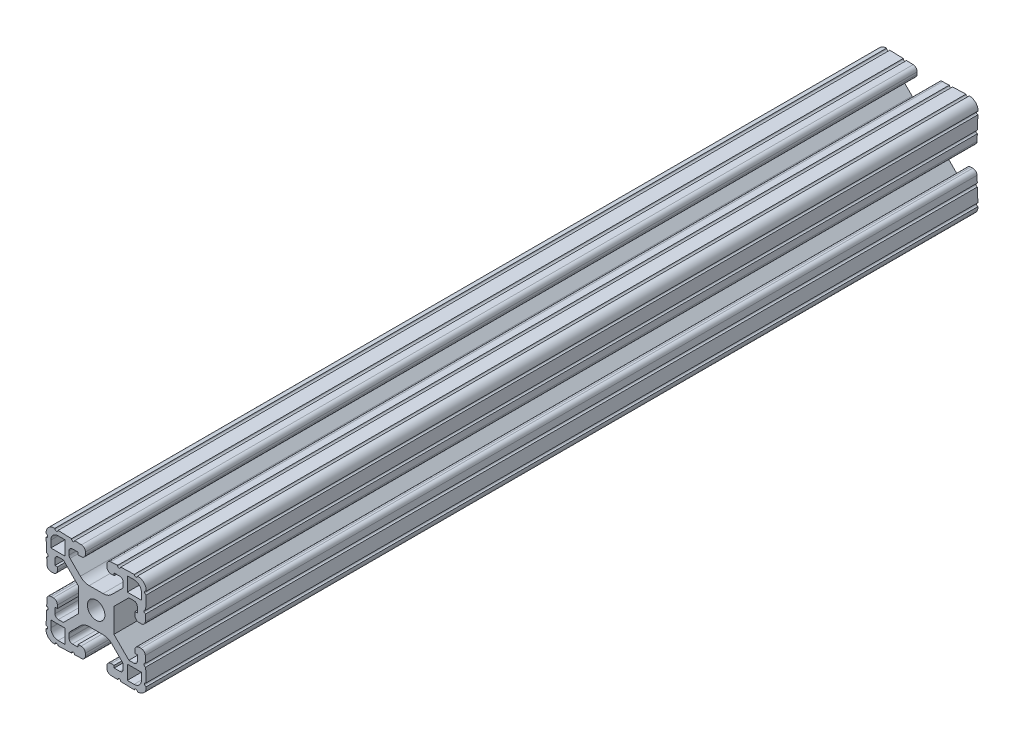
SolidWorks part; units mm, degrees
ref_plane "Front Plane" through (0, 0, 0) normal (0, 0, 1) x (1, 0, 0)
ref_plane "Top Plane" through (0, 0, 0) normal (0, 1, 0) x (1, 0, 0)
ref_plane "Right Plane" through (0, 0, 0) normal (1, 0, 0) x (0, 0, -1)
sketch "Sketch1" plane through (0, 0, 0) normal (0, 0, 1) x (1, 0, 0)
  line L0 (0, 19.05) -> (-19.1669, 19.05) construction
  line L1 (-6.7564, 0) -> (-6.7564, 4.6011)
  line L2 (-8.7357, 18.8026) -> (-15.7642, 19.0481) construction
  line L3 (-17.655, 18.5041) -> (-4.0303, 18.0283) construction
  line L4 (-5.5829, 18.6925) -> (-5.7212, 14.7325) construction
  line L5 (-11.8364, 17.2212) -> (-11.8364, 11.8364)
  line L6 (-2.6337, 6.7564) -> (0, 6.7564)
  line L7 (0, 0) -> (0, 19.05) construction
  line L8 (0, 0) -> (-19.1669, 0) construction
  line L9 (1.0776, 1.0776) -> (-1.0776, -1.0776) construction
  line L10 (-5.9923, 8.1476) -> (-9.915, 12.0703)
  line L11 (-6.7564, 4.6011) -> (-12.4423, 10.287)
  line L12 (-11.8364, 11.8364) -> (-17.2212, 11.8364)
  line L13 (0, 0) -> (-19.1669, 19.1669) construction
  line L14 (-15.7642, 19.0481) -> (-5.5829, 18.6925)
  line L15 (-4.064, 17.0637) -> (-4.0924, 16.2514)
  line L17 (-19.0481, 15.7642) -> (-18.6925, 5.5829)
  line L19 (-17.2212, 11.8364) -> (-17.2212, 14.4272)
  line L20 (-11.8364, 17.2212) -> (-14.4272, 17.2212)
  line L21 (-10.287, 12.9683) -> (-10.287, 14.3745)
  line L22 (-14.3745, 10.287) -> (-12.4423, 10.287)
  line L23 (-9.017, 15.6445) -> (-6.858, 15.6445)
  line L24 (-6.858, 15.6445) -> (-6.858, 14.7325)
  line L25 (-5.7212, 14.7325) -> (-6.858, 14.7325)
  line L26 (-17.0637, 4.064) -> (-16.2514, 4.0924)
  line L27 (-14.7325, 5.7212) -> (-14.7325, 6.858)
  line L28 (-15.6445, 6.858) -> (-14.7325, 6.858)
  line L29 (-15.6445, 9.017) -> (-15.6445, 6.858)
  circle A0 centre (0, 0) radius 3.3274
  arc A5 (-15.7642, 19.0481) -> (-19.0481, 15.7642) centre (-15.875, 15.875) ccw
  arc A7 (-9.3449, 18.8239) -> (-8.1264, 18.7813) centre (-8.7357, 18.8026) ccw
  arc A10 (-17.2212, 14.4272) -> (-14.4272, 17.2212) centre (-14.4272, 14.4272) cw
  arc A11 (-4.0924, 16.2514) -> (-5.7212, 14.7325) centre (-5.6662, 16.3064) cw
  arc A12 (-5.5829, 18.6925) -> (-4.064, 17.0637) centre (-5.6378, 17.1187) cw
  arc A13 (-5.9923, 8.1476) -> (-2.6337, 6.7564) centre (-2.6337, 11.5062) ccw
  arc A14 (-9.915, 12.0703) -> (-10.287, 12.9683) centre (-9.017, 12.9683) cw
  arc A15 (-10.287, 14.3745) -> (-9.017, 15.6445) centre (-9.017, 14.3745) cw
  arc A16 (-15.6949, 19.0456) -> (-14.4764, 19.0031) centre (-15.0857, 19.0244) ccw
  arc A17 (-18.6925, 5.5829) -> (-17.0637, 4.064) centre (-17.1187, 5.6378) ccw
  arc A18 (-16.2514, 4.0924) -> (-14.7325, 5.7212) centre (-16.3064, 5.6662) ccw
  arc A19 (-14.3745, 10.287) -> (-15.6445, 9.017) centre (-14.3745, 9.017) ccw
  arc A20 (-18.8239, 9.3449) -> (-18.7813, 8.1264) centre (-18.8026, 8.7357) cw
  arc A21 (-19.0456, 15.6949) -> (-19.0031, 14.4764) centre (-19.0244, 15.0857) cw
  point P27 (-5.7298, 13.1063)
  point P49 (-4.009, 18.6376)
  point P55 (-10.287, 12.4423)
  dimension "D1" = 6.6548
  dimension "D10" = 3.175
  dimension "D13" = 2.794
  dimension "D7" = 1.5748
  dimension "D20" = 4.7498
  dimension "D21" = 1.27
  dimension "D3" = 13.5128
  dimension "D4" = 13.5128
  dimension "D8" = 3.048
  dimension "D6" = 38.1
  dimension "D9" = 2
  dimension "D2" = 38.1
  dimension "D11" = 19.05
  dimension "D5" = 20.574
  dimension "D14" = 7.2136
  dimension "D15" = 5.3848
  dimension "D16" = 3.9624
  dimension "D17" = 3.048
  dimension "D18" = 8.128
  dimension "D22" = 10.3124
  dimension "D23" = 3.9624
  dimension "D12" = 0.6096
  dimension "D19" = 13.716
sketch "Sketch3" plane through (0, 0, 0) normal (0, 0, 1) x (1, 0, 0)
  line L8 (-2.6337, 6.7564) -> (0, 6.7564) construction
  line L9 (-5.9923, 8.1476) -> (-9.915, 12.0703) construction
  line L10 (-10.287, 12.9683) -> (-10.287, 14.3745) construction
  line L11 (-9.017, 15.6445) -> (-6.858, 15.6445) construction
  line L12 (-6.858, 15.6445) -> (-6.858, 14.7325) construction
  line L13 (-5.7212, 14.7325) -> (-6.858, 14.7325) construction
  line L14 (-4.064, 17.0637) -> (-4.0924, 16.2514) construction
  line L15 (-15.7642, 19.0481) -> (-5.5829, 18.6925) construction
  line L16 (-19.0481, 15.7642) -> (-18.6925, 5.5829) construction
  line L17 (-17.0637, 4.064) -> (-16.2514, 4.0924) construction
  line L18 (-14.7325, 5.7212) -> (-14.7325, 6.858) construction
  line L19 (-15.6445, 6.858) -> (-14.7325, 6.858) construction
  line L20 (-15.6445, 9.017) -> (-15.6445, 6.858) construction
  line L21 (-14.3745, 10.287) -> (-12.4423, 10.287) construction
  line L22 (-6.7564, 4.6011) -> (-12.4423, 10.287) construction
  line L23 (-6.7564, 0) -> (-6.7564, 4.6011) construction
  line L24 (-2.6337, 6.7564) -> (2.6337, 6.7564)
  line L25 (-5.9923, 8.1476) -> (-9.915, 12.0703)
  line L26 (-10.287, 12.9683) -> (-10.287, 14.3745)
  line L27 (-9.017, 15.6445) -> (-6.858, 15.6445)
  line L28 (-6.858, 15.6445) -> (-6.858, 14.7325)
  line L29 (-5.7212, 14.7325) -> (-6.858, 14.7325)
  line L30 (-4.064, 17.0637) -> (-4.0924, 16.2514)
  line L31 (-15.7642, 19.0481) -> (-15.6949, 19.0456)
  line L32 (-19.0481, 15.7642) -> (-19.0456, 15.6949)
  line L33 (-17.0637, 4.064) -> (-16.2514, 4.0924)
  line L34 (-14.7325, 5.7212) -> (-14.7325, 6.858)
  line L35 (-15.6445, 6.858) -> (-14.7325, 6.858)
  line L36 (-15.6445, 9.017) -> (-15.6445, 6.858)
  line L37 (-14.3745, 10.287) -> (-12.4423, 10.287)
  line L38 (-6.7564, 4.6011) -> (-12.4423, 10.287)
  line L39 (-6.7564, -4.6011) -> (-6.7564, 4.6011)
  line L40 (0, 0) -> (-6.7564, 0) construction
  line L41 (0, 0) -> (0, 6.7564) construction
  line L42 (-8.1264, 18.7813) -> (-5.5829, 18.6925)
  line L43 (-14.4764, 19.0031) -> (-9.3449, 18.8239)
  line L48 (-11.8364, 11.8364) -> (-11.8364, 17.2212)
  line L49 (-17.2212, 11.8364) -> (-11.8364, 11.8364)
  line L50 (-17.2212, 14.4272) -> (-17.2212, 11.8364)
  line L51 (-11.8364, 17.2212) -> (-14.4272, 17.2212)
  line L52 (-19.0031, 14.4764) -> (-18.8239, 9.3449)
  line L53 (-18.7813, 8.1264) -> (-18.6925, 5.5829)
  line L54 (18.7813, 8.1264) -> (18.6925, 5.5829)
  line L55 (19.0031, 14.4764) -> (18.8239, 9.3449)
  line L56 (11.8364, 17.2212) -> (14.4272, 17.2212)
  line L57 (17.2212, 14.4272) -> (17.2212, 11.8364)
  line L58 (17.2212, 11.8364) -> (11.8364, 11.8364)
  line L59 (11.8364, 11.8364) -> (11.8364, 17.2212)
  line L60 (14.4764, 19.0031) -> (9.3449, 18.8239)
  line L61 (8.1264, 18.7813) -> (5.5829, 18.6925)
  line L62 (6.7564, -4.6011) -> (6.7564, 4.6011)
  line L63 (6.7564, 4.6011) -> (12.4423, 10.287)
  line L64 (14.3745, 10.287) -> (12.4423, 10.287)
  line L65 (15.6445, 9.017) -> (15.6445, 6.858)
  line L66 (15.6445, 6.858) -> (14.7325, 6.858)
  line L67 (14.7325, 5.7212) -> (14.7325, 6.858)
  line L68 (17.0637, 4.064) -> (16.2514, 4.0924)
  line L69 (19.0481, 15.7642) -> (19.0456, 15.6949)
  line L70 (15.7642, 19.0481) -> (15.6949, 19.0456)
  line L71 (4.064, 17.0637) -> (4.0924, 16.2514)
  line L72 (5.7212, 14.7325) -> (6.858, 14.7325)
  line L73 (6.858, 15.6445) -> (6.858, 14.7325)
  line L74 (9.017, 15.6445) -> (6.858, 15.6445)
  line L75 (10.287, 12.9683) -> (10.287, 14.3745)
  line L76 (5.9923, 8.1476) -> (9.915, 12.0703)
  line L77 (5.9923, -8.1476) -> (9.915, -12.0703)
  line L78 (10.287, -12.9683) -> (10.287, -14.3745)
  line L79 (9.017, -15.6445) -> (6.858, -15.6445)
  line L80 (6.858, -15.6445) -> (6.858, -14.7325)
  line L81 (5.7212, -14.7325) -> (6.858, -14.7325)
  line L82 (4.064, -17.0637) -> (4.0924, -16.2514)
  line L83 (15.7642, -19.0481) -> (15.6949, -19.0456)
  line L84 (19.0481, -15.7642) -> (19.0456, -15.6949)
  line L85 (17.0637, -4.064) -> (16.2514, -4.0924)
  line L86 (14.7325, -5.7212) -> (14.7325, -6.858)
  line L87 (15.6445, -6.858) -> (14.7325, -6.858)
  line L88 (15.6445, -9.017) -> (15.6445, -6.858)
  line L89 (14.3745, -10.287) -> (12.4423, -10.287)
  line L90 (6.7564, -4.6011) -> (12.4423, -10.287)
  line L91 (8.1264, -18.7813) -> (5.5829, -18.6925)
  line L92 (14.4764, -19.0031) -> (9.3449, -18.8239)
  line L93 (11.8364, -11.8364) -> (11.8364, -17.2212)
  line L94 (17.2212, -11.8364) -> (11.8364, -11.8364)
  line L95 (17.2212, -14.4272) -> (17.2212, -11.8364)
  line L96 (11.8364, -17.2212) -> (14.4272, -17.2212)
  line L97 (19.0031, -14.4764) -> (18.8239, -9.3449)
  line L98 (18.7813, -8.1264) -> (18.6925, -5.5829)
  line L99 (-18.7813, -8.1264) -> (-18.6925, -5.5829)
  line L100 (-19.0031, -14.4764) -> (-18.8239, -9.3449)
  line L101 (-11.8364, -17.2212) -> (-14.4272, -17.2212)
  line L102 (-17.2212, -14.4272) -> (-17.2212, -11.8364)
  line L103 (-17.2212, -11.8364) -> (-11.8364, -11.8364)
  line L104 (-11.8364, -11.8364) -> (-11.8364, -17.2212)
  line L105 (-14.4764, -19.0031) -> (-9.3449, -18.8239)
  line L106 (-8.1264, -18.7813) -> (-5.5829, -18.6925)
  line L107 (-6.7564, -4.6011) -> (-12.4423, -10.287)
  line L108 (-14.3745, -10.287) -> (-12.4423, -10.287)
  line L109 (-15.6445, -9.017) -> (-15.6445, -6.858)
  line L110 (-15.6445, -6.858) -> (-14.7325, -6.858)
  line L111 (-14.7325, -5.7212) -> (-14.7325, -6.858)
  line L112 (-17.0637, -4.064) -> (-16.2514, -4.0924)
  line L113 (-19.0481, -15.7642) -> (-19.0456, -15.6949)
  line L114 (-15.7642, -19.0481) -> (-15.6949, -19.0456)
  line L115 (-4.064, -17.0637) -> (-4.0924, -16.2514)
  line L116 (-5.7212, -14.7325) -> (-6.858, -14.7325)
  line L117 (-6.858, -15.6445) -> (-6.858, -14.7325)
  line L118 (-9.017, -15.6445) -> (-6.858, -15.6445)
  line L119 (-10.287, -12.9683) -> (-10.287, -14.3745)
  line L120 (-5.9923, -8.1476) -> (-9.915, -12.0703)
  line L121 (-2.6337, -6.7564) -> (2.6337, -6.7564)
  arc A9 (-15.6949, 19.0456) -> (-14.4764, 19.0031) centre (-15.0857, 19.0244) ccw construction
  arc A10 (-5.9923, 8.1476) -> (-2.6337, 6.7564) centre (-2.6337, 11.5062) ccw construction
  arc A11 (-10.287, 12.9683) -> (-9.915, 12.0703) centre (-9.017, 12.9683) ccw construction
  arc A12 (-9.017, 15.6445) -> (-10.287, 14.3745) centre (-9.017, 14.3745) ccw construction
  arc A13 (-5.7212, 14.7325) -> (-4.0924, 16.2514) centre (-5.6662, 16.3064) ccw construction
  arc A14 (-4.064, 17.0637) -> (-5.5829, 18.6925) centre (-5.6378, 17.1187) ccw construction
  arc A15 (-15.7642, 19.0481) -> (-19.0481, 15.7642) centre (-15.875, 15.875) ccw construction
  arc A16 (-18.6925, 5.5829) -> (-17.0637, 4.064) centre (-17.1187, 5.6378) ccw construction
  arc A17 (-16.2514, 4.0924) -> (-14.7325, 5.7212) centre (-16.3064, 5.6662) ccw construction
  arc A18 (-14.3745, 10.287) -> (-15.6445, 9.017) centre (-14.3745, 9.017) ccw construction
  arc A19 (-9.3449, 18.8239) -> (-8.1264, 18.7813) centre (-8.7357, 18.8026) ccw construction
  arc A20 (-18.7813, 8.1264) -> (-18.8239, 9.3449) centre (-18.8026, 8.7357) ccw construction
  arc A21 (-19.0031, 14.4764) -> (-19.0456, 15.6949) centre (-19.0244, 15.0857) ccw construction
  arc A22 (-15.6949, 19.0456) -> (-14.4764, 19.0031) centre (-15.0857, 19.0244) ccw
  arc A23 (-5.9923, 8.1476) -> (-2.6337, 6.7564) centre (-2.6337, 11.5062) ccw
  arc A24 (-10.287, 12.9683) -> (-9.915, 12.0703) centre (-9.017, 12.9683) ccw
  arc A25 (-9.017, 15.6445) -> (-10.287, 14.3745) centre (-9.017, 14.3745) ccw
  arc A26 (-5.7212, 14.7325) -> (-4.0924, 16.2514) centre (-5.6662, 16.3064) ccw
  arc A27 (-4.064, 17.0637) -> (-5.5829, 18.6925) centre (-5.6378, 17.1187) ccw
  arc A28 (-15.7642, 19.0481) -> (-19.0481, 15.7642) centre (-15.875, 15.875) ccw
  arc A29 (-18.6925, 5.5829) -> (-17.0637, 4.064) centre (-17.1187, 5.6378) ccw
  arc A30 (-16.2514, 4.0924) -> (-14.7325, 5.7212) centre (-16.3064, 5.6662) ccw
  arc A31 (-14.3745, 10.287) -> (-15.6445, 9.017) centre (-14.3745, 9.017) ccw
  arc A32 (-9.3449, 18.8239) -> (-8.1264, 18.7813) centre (-8.7357, 18.8026) ccw
  arc A33 (-18.7813, 8.1264) -> (-18.8239, 9.3449) centre (-18.8026, 8.7357) ccw
  arc A34 (-19.0031, 14.4764) -> (-19.0456, 15.6949) centre (-19.0244, 15.0857) ccw
  arc A35 (14.4272, 17.2212) -> (17.2212, 14.4272) centre (14.4272, 14.4272) cw
  circle A36 centre (0, 0) radius 3.3274
  circle A37 centre (0, 0) radius 3.3274
  arc A39 (-14.4272, 17.2212) -> (-17.2212, 14.4272) centre (-14.4272, 14.4272) ccw
  arc A40 (19.0031, 14.4764) -> (19.0456, 15.6949) centre (19.0244, 15.0857) cw
  arc A41 (18.7813, 8.1264) -> (18.8239, 9.3449) centre (18.8026, 8.7357) cw
  arc A42 (9.3449, 18.8239) -> (8.1264, 18.7813) centre (8.7357, 18.8026) cw
  arc A43 (14.3745, 10.287) -> (15.6445, 9.017) centre (14.3745, 9.017) cw
  arc A44 (16.2514, 4.0924) -> (14.7325, 5.7212) centre (16.3064, 5.6662) cw
  arc A45 (18.6925, 5.5829) -> (17.0637, 4.064) centre (17.1187, 5.6378) cw
  arc A46 (15.7642, 19.0481) -> (19.0481, 15.7642) centre (15.875, 15.875) cw
  arc A47 (4.064, 17.0637) -> (5.5829, 18.6925) centre (5.6378, 17.1187) cw
  arc A48 (5.7212, 14.7325) -> (4.0924, 16.2514) centre (5.6662, 16.3064) cw
  arc A49 (9.017, 15.6445) -> (10.287, 14.3745) centre (9.017, 14.3745) cw
  arc A50 (10.287, 12.9683) -> (9.915, 12.0703) centre (9.017, 12.9683) cw
  arc A51 (5.9923, 8.1476) -> (2.6337, 6.7564) centre (2.6337, 11.5062) cw
  arc A52 (15.6949, 19.0456) -> (14.4764, 19.0031) centre (15.0857, 19.0244) cw
  arc A54 (15.6949, -19.0456) -> (14.4764, -19.0031) centre (15.0857, -19.0244) ccw
  arc A55 (5.9923, -8.1476) -> (2.6337, -6.7564) centre (2.6337, -11.5062) ccw
  arc A56 (10.287, -12.9683) -> (9.915, -12.0703) centre (9.017, -12.9683) ccw
  arc A57 (9.017, -15.6445) -> (10.287, -14.3745) centre (9.017, -14.3745) ccw
  arc A58 (5.7212, -14.7325) -> (4.0924, -16.2514) centre (5.6662, -16.3064) ccw
  arc A59 (4.064, -17.0637) -> (5.5829, -18.6925) centre (5.6378, -17.1187) ccw
  arc A60 (15.7642, -19.0481) -> (19.0481, -15.7642) centre (15.875, -15.875) ccw
  arc A61 (18.6925, -5.5829) -> (17.0637, -4.064) centre (17.1187, -5.6378) ccw
  arc A62 (16.2514, -4.0924) -> (14.7325, -5.7212) centre (16.3064, -5.6662) ccw
  arc A63 (14.3745, -10.287) -> (15.6445, -9.017) centre (14.3745, -9.017) ccw
  arc A64 (9.3449, -18.8239) -> (8.1264, -18.7813) centre (8.7357, -18.8026) ccw
  arc A65 (18.7813, -8.1264) -> (18.8239, -9.3449) centre (18.8026, -8.7357) ccw
  arc A66 (19.0031, -14.4764) -> (19.0456, -15.6949) centre (19.0244, -15.0857) ccw
  arc A67 (-14.4272, -17.2212) -> (-17.2212, -14.4272) centre (-14.4272, -14.4272) cw
  arc A68 (14.4272, -17.2212) -> (17.2212, -14.4272) centre (14.4272, -14.4272) ccw
  arc A69 (-19.0031, -14.4764) -> (-19.0456, -15.6949) centre (-19.0244, -15.0857) cw
  arc A70 (-18.7813, -8.1264) -> (-18.8239, -9.3449) centre (-18.8026, -8.7357) cw
  arc A71 (-9.3449, -18.8239) -> (-8.1264, -18.7813) centre (-8.7357, -18.8026) cw
  arc A72 (-14.3745, -10.287) -> (-15.6445, -9.017) centre (-14.3745, -9.017) cw
  arc A73 (-16.2514, -4.0924) -> (-14.7325, -5.7212) centre (-16.3064, -5.6662) cw
  arc A74 (-18.6925, -5.5829) -> (-17.0637, -4.064) centre (-17.1187, -5.6378) cw
  arc A75 (-15.7642, -19.0481) -> (-19.0481, -15.7642) centre (-15.875, -15.875) cw
  arc A76 (-4.064, -17.0637) -> (-5.5829, -18.6925) centre (-5.6378, -17.1187) cw
  arc A77 (-5.7212, -14.7325) -> (-4.0924, -16.2514) centre (-5.6662, -16.3064) cw
  arc A78 (-9.017, -15.6445) -> (-10.287, -14.3745) centre (-9.017, -14.3745) cw
  arc A79 (-10.287, -12.9683) -> (-9.915, -12.0703) centre (-9.017, -12.9683) cw
  arc A80 (-5.9923, -8.1476) -> (-2.6337, -6.7564) centre (-2.6337, -11.5062) cw
  arc A81 (-15.6949, -19.0456) -> (-14.4764, -19.0031) centre (-15.0857, -19.0244) cw
  point P201 (6.7564, 0)
  dimension "D1" = 0
extrude "Extrude1" add sketch "Sketch3" along normal mid plane 316.0674
ref_plane "Plane1" through (0, 19.0456, 0) normal (0, -1, 0) x (-1, 0, 0)
ref_plane "Plane2" through (19.0456, 0, 0) normal (-1, 0, 0) x (0, 0, 1)
ref_plane "Plane3" through (0, -19.0456, 0) normal (0, 1, 0) x (1, 0, 0)
ref_plane "Plane4" through (-19.0456, 0, 0) normal (1, 0, 0) x (0, 0, -1)
ref_plane "Plane5" through (0, 0, 0) normal (-1, 0, 0) x (0, 0, 1)
ref_plane "Plane6" through (0, 0, 0) normal (0, 1, 0) x (1, 0, 0)
equation "\"D11@Sketch1\" = \"D6@Sketch1\"/2"
equation "\"D16@Sketch1\" = \"D8@Sketch1\"*1.3"
equation "\"D17@Sketch1\" = \"D8@Sketch1\""
equation "\"D12@Sketch1\" = \"D8@Sketch1\"/5"
